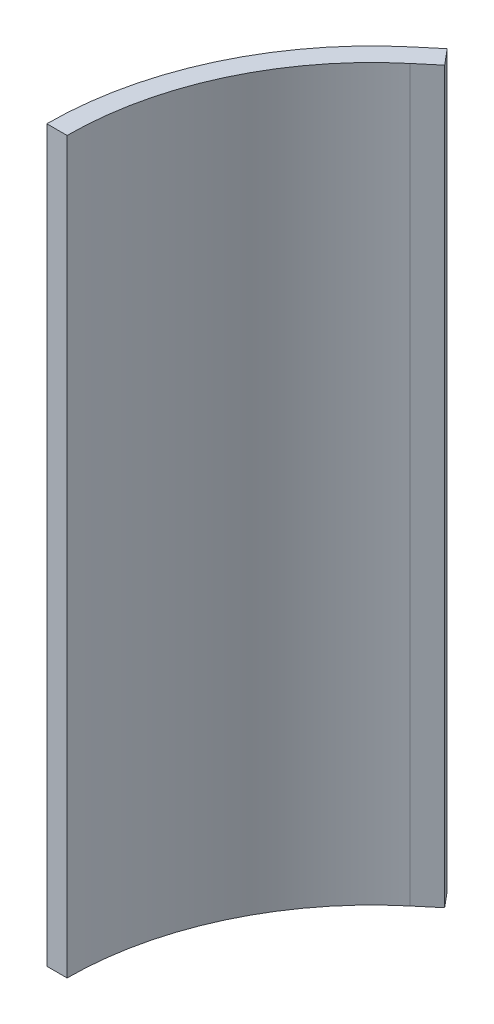
SolidWorks part; units mm, degrees
material "Custom Plastic"
ref_plane "Front Plane" through (0, 0, 0) normal (0, 0, 1) x (1, 0, 0)
ref_plane "Top Plane" through (0, 0, 0) normal (0, 1, 0) x (1, 0, 0)
ref_plane "Right Plane" through (0, 0, 0) normal (1, 0, 0) x (0, 0, -1)
sketch "Sketch1" plane through (0, 0, 0) normal (0, 1, 0) x (1, 0, 0)
  line L0 (0, 0) -> (77.7862, 0) construction
  line L1 (77.7862, 0) -> (77.7862, 50) construction
  line L2 (0, 0) -> (0, -10) construction
  line L3 (23.3154, 50) -> (-36.2723, 0) construction
  line L4 (10, 0) -> (-10, 0)
  line L5 (29.7433, 42.3396) -> (16.8875, 57.6604)
  arc A0 (0, 0) -> (23.3154, 50) centre (65.2704, 0) cw construction
  arc A1 (10, 0) -> (29.7433, 42.3396) centre (65.2704, 0) cw
  arc A2 (-10, 0) -> (16.8875, 57.6604) centre (65.2704, 0) cw
  circle A3 centre (0.7706, 10) radius 2.6
  circle A4 centre (6.1153, 27.5844) radius 2.6
  circle A5 centre (16.1503, 42.9818) radius 2.6
  circle A7 centre (30.0798, 54.9713) radius 2.6 [skipped]
  point P24 (65.2704, 0)
  dimension "D6" = 5.2
  dimension "D9" = 10
  dimension "D1" = 10
  dimension "D2" = 40
  dimension "D3" = 50
  dimension "D7" = 10
  dimension "D8" = 4
  dimension "D4" = 10
  dimension "D5" = 10
extrude "Boss-Extrude1" add sketch "Sketch1" along normal blind 20
sketch "Sketch2" plane through (0, 20, 0) normal (0, 1, 0) x (1, 0, 0)
  line L0 (16.8875, 57.6604) -> (29.7433, 42.3396)
  line L1 (16.8875, 57.6604) -> (21.5604, 61.5814)
  line L2 (29.7433, 42.3396) -> (34.4161, 46.2606)
  line L3 (21.5604, 61.5814) -> (34.4161, 46.2606)
  dimension "D1" = 6.1
extrude "Boss-Extrude2" add sketch "Sketch2" against normal up to surface (20 mm away) up to face at (0.7706, 0, -7.4)
sketch "Sketch3" plane through (0, 20, 0) normal (0, 1, 0) x (1, 0, 0)
  line L5 (21.5604, 61.5814) -> (16.8875, 57.6604) construction
  line L6 (18.3464, 65.4117) -> (13.6736, 61.4907)
  line L7 (18.3464, 65.4117) -> (13.6736, 61.4907)
  line L8 (21.5604, 61.5814) -> (16.8875, 57.6604)
  line L9 (-15, 0) -> (-10, 0)
  line L10 (18.3464, 65.4117) -> (21.5604, 61.5814)
  arc A4 (16.8875, 57.6604) -> (-10, 0) centre (65.2704, 0) ccw construction
  arc A5 (13.6736, 61.4907) -> (-15, 0) centre (65.2704, 0) ccw
  arc A6 (13.6736, 61.4907) -> (-15, 0) centre (65.2704, 0) ccw
  arc A7 (16.8875, 57.6604) -> (-10, 0) centre (65.2704, 0) ccw
  dimension "D1" = 5
extrude "Boss-Extrude3" add sketch "Sketch3" along normal blind 180 separate body
sketch "Sketch4" plane through (0, 20, 0) normal (0, 1, 0) x (1, 0, 0)
  line L4 (29.7433, 42.3396) -> (34.4161, 46.2606)
  line L5 (34.4161, 46.2606) -> (21.5604, 61.5814)
  line L6 (21.5604, 61.5814) -> (16.8875, 57.6604)
  line L7 (-10, 0) -> (10, 0)
  line L8 (29.7433, 42.3396) -> (34.4161, 46.2606)
  line L9 (34.4161, 46.2606) -> (21.5604, 61.5814)
  line L10 (21.5604, 61.5814) -> (16.8875, 57.6604)
  line L11 (-10, 0) -> (10, 0)
  arc A2 (29.7433, 42.3396) -> (10, 0) centre (65.2704, 0) ccw
  arc A3 (16.8875, 57.6604) -> (-10, 0) centre (65.2704, 0) ccw
  arc A4 (29.7433, 42.3396) -> (10, 0) centre (65.2704, 0) ccw
  arc A5 (16.8875, 57.6604) -> (-10, 0) centre (65.2704, 0) ccw
  dimension "D1" = 0
extrude "Cut-Extrude1" cut sketch "Sketch4" against normal through all
